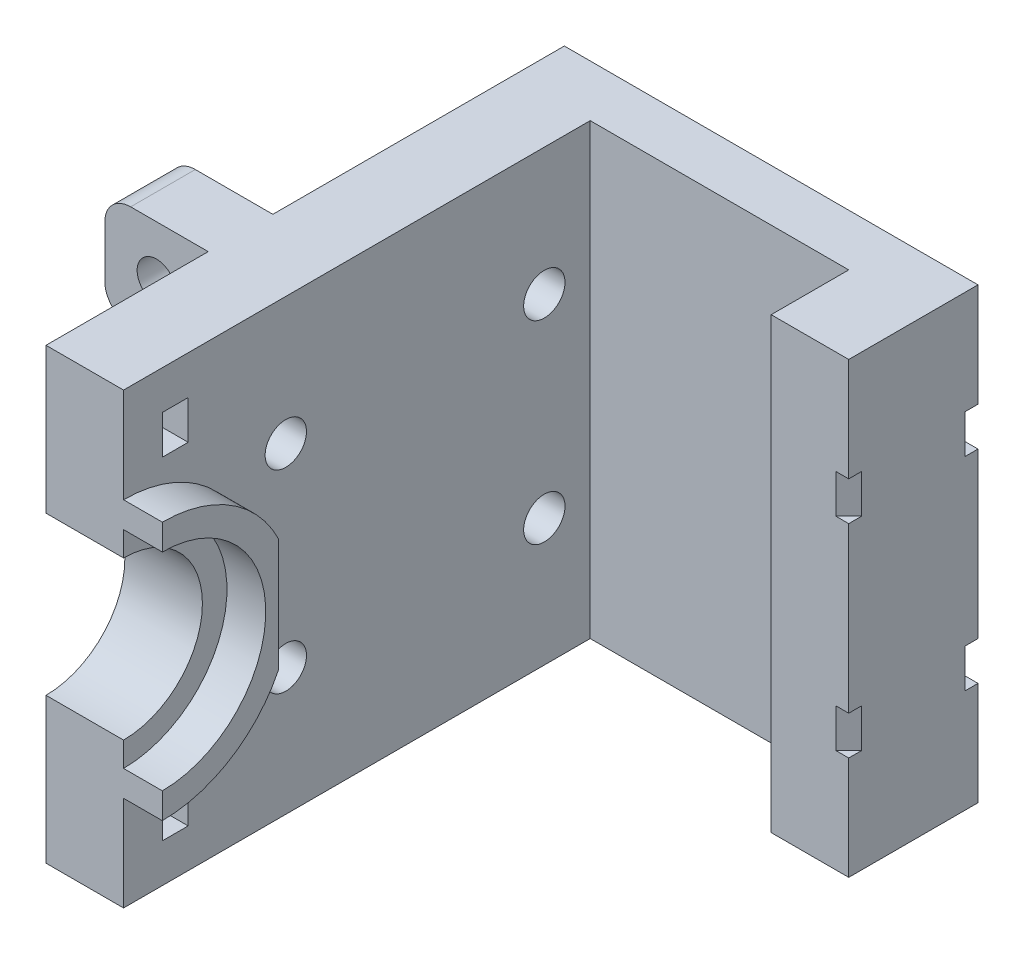
SolidWorks part; units mm, degrees
ref_plane "前基準面" through (0, 0, 0) normal (0, 0, 1) x (1, 0, 0)
ref_plane "上基準面" through (0, 0, 0) normal (0, 1, 0) x (1, 0, 0)
ref_plane "右基準面" through (0, 0, 0) normal (1, 0, 0) x (0, 0, -1)
sketch "草圖2" plane through (0, 0, 0) normal (1, 0, 0) x (0, 0, -1)
  line L1 (-13.55, 17.35) -> (13.55, 17.35)
  line L2 (-13.55, 17.35) -> (-13.55, -17.35) construction
  line L3 (-13.55, -17.35) -> (13.55, -17.35)
  line L4 (13.55, 17.35) -> (13.55, -17.35)
  line L5 (-13.55, 17.35) -> (13.55, -17.35) construction
  line L6 (-13.55, -17.35) -> (13.55, 17.35) construction
  line L7 (-10, 7.5) -> (10, 7.5) construction
  line L8 (-10, 7.5) -> (-10, -7.5) construction
  line L9 (-10, -7.5) -> (10, -7.5) construction
  line L10 (10, 7.5) -> (10, -7.5) construction
  line L11 (-10, 7.5) -> (10, -7.5) construction
  line L12 (-10, -7.5) -> (10, 7.5) construction
  line L13 (-13.55, 17.35) -> (-22.55, 17.35)
  line L14 (-13.55, 17.35) -> (-13.55, -17.35) construction
  line L15 (-13.55, -17.35) -> (-22.55, -17.35)
  line L16 (-22.55, 17.35) -> (-22.55, -17.35)
  line L17 (-19.55, -14.35) -> (-17.55, -14.35)
  line L18 (-19.55, -14.35) -> (-19.55, -11.35)
  line L19 (-19.55, -11.35) -> (-17.55, -11.35)
  line L20 (-17.55, -14.35) -> (-17.55, -11.35)
  line L21 (-19.55, 14.35) -> (-17.55, 14.35)
  line L22 (-19.55, 14.35) -> (-19.55, 11.35)
  line L23 (-19.55, 11.35) -> (-17.55, 11.35)
  line L24 (-17.55, 14.35) -> (-17.55, 11.35)
  circle A0 centre (-10, 7.5) radius 1.6
  circle A1 centre (10, 7.5) radius 1.6
  circle A2 centre (10, -7.5) radius 1.6
  circle A3 centre (-10, -7.5) radius 1.6
  arc A4 (-22.55, -6.1) -> (-22.55, 6.1) centre (-22.55, 0) ccw
  point P0 (0, 0)
  point P6 (0, 0)
  dimension "D5" = 3.2
  dimension "D6" = 3.2
  dimension "D7" = 3.2
  dimension "D8" = 3.2
  dimension "D10" = 6.1
  dimension "D1" = 27.1
  dimension "D2" = 34.7
  dimension "D3" = 20
  dimension "D4" = 15
  dimension "D9" = 9
  dimension "D11" = 2
  dimension "D12" = 3
  dimension "D13" = 3
  dimension "D14" = 3
  dimension "D15" = 3
  dimension "D16" = 3
  dimension "D17" = 3
  dimension "D18" = 2
extrude "填料-伸長1" add sketch "草圖2" along normal blind 6 contours A4 L16 L15 L3 L4 L1 L13 A3 A2 A1 A0 L20 L17 L18 L19 L21 L24 L23 L22
sketch "草圖3" plane through (6, 0, 0) normal (1, 0, 0) x (0, 0, -1)
  line L0 (-22.55, -6.1) -> (-22.55, -17.35) construction
  line L1 (-22.55, 17.35) -> (-22.55, 6.1) construction
  line L2 (-13.55, 4.3589) -> (-13.55, -4.3589)
  line L4 (-22.55, 10) -> (-22.55, 8)
  line L5 (-22.55, -8) -> (-22.55, -10)
  arc A0 (-22.55, -8) -> (-22.55, 8) centre (-22.55, 0) ccw
  arc A1 (-22.55, -10) -> (-13.55, -4.3589) centre (-22.55, 0) ccw
  arc A2 (-13.55, 4.3589) -> (-22.55, 10) centre (-22.55, 0) ccw
  dimension "D1" = 8
  dimension "D2" = 10
  dimension "D3" = 9
extrude "填料-伸長2" add sketch "草圖3" along normal blind 3
sketch "草圖4" plane through (0, 0, 0) normal (-1, 0, 0) x (0, 0, 1)
  line L1 (-13.55, 17.35) -> (-17.55, 17.35)
  line L2 (-13.55, 17.35) -> (-13.55, -17.35)
  line L3 (-13.55, -17.35) -> (-17.55, -17.35)
  line L4 (-17.55, 17.35) -> (-17.55, -17.35)
  dimension "D1" = 4
extrude "填料-伸長3" add sketch "草圖4" against normal blind 26
sketch "草圖5" plane through (26, 0, 0) normal (1, 0, 0) x (0, 0, -1)
  line L0 (13.55, -17.35) -> (-22.55, -17.35) construction
  line L1 (17.55, 17.35) -> (6.55, 17.35)
  line L2 (17.55, 17.35) -> (17.55, -17.35)
  line L3 (17.55, -17.35) -> (6.55, -17.35)
  line L4 (6.55, 17.35) -> (6.55, -17.35)
  dimension "D1" = 11
ref_plane "平面1" through (0, -9.35, 0) normal (0, -1, 0) x (-1, 0, 0)
ref_plane "平面2" through (0, 9.35, 0) normal (0, 1, 0) x (1, 0, 0)
sketch "草圖10" plane through (0, 0, 0) normal (-1, 0, 0) x (0, 0, 1)
  line L1 (-17.55, 17.35) -> (-21.55, 17.35)
  line L2 (-17.55, 17.35) -> (-17.55, -17.35)
  line L3 (-17.55, -17.35) -> (-21.55, -17.35)
  line L4 (-21.55, 17.35) -> (-21.55, -17.35)
  dimension "D1" = 4
sketch "草圖15" plane through (26, 0, 0) normal (1, 0, 0) x (0, 0, -1)
  line L0 (17.55, -17.35) -> (6.55, -17.35) construction
  line L1 (17.55, 17.35) -> (7.55, 17.35)
  line L2 (17.55, 17.35) -> (17.55, -17.35)
  line L3 (17.55, -17.35) -> (7.55, -17.35)
  line L4 (7.55, 17.35) -> (7.55, -17.35)
  dimension "D1" = 10
extrude "填料-伸長8" add sketch "草圖15" along normal blind 6
sketch "草圖16" plane through (0, 0, -17.55) normal (0, 0, -1) x (-1, 0, 0)
  line L0 (-26, 17.35) -> (-26, -17.35) construction
  line L1 (-26, 9.35) -> (-24, 9.35)
  line L2 (-26, 9.35) -> (-26, 6.35)
  line L3 (-26, 6.35) -> (-24, 6.35)
  line L4 (-24, 9.35) -> (-24, 6.35)
  line L5 (14.3, 9.35) -> (-14.3, 9.35) construction
  line L6 (-14.3, -9.35) -> (14.3, -9.35) construction
  line L7 (-26, -9.35) -> (-24, -9.35)
  line L8 (-26, -9.35) -> (-26, -6.35)
  line L9 (-26, -6.35) -> (-24, -6.35)
  line L10 (-24, -9.35) -> (-24, -6.35)
  dimension "D1" = 2
  dimension "D2" = 3
  dimension "D3" = 2
  dimension "D4" = 3
extrude "除料-伸長4" cut sketch "草圖16" against normal blind 6
sketch "草圖17" plane through (0, -9.35, 0) normal (0, -1, 0) x (-1, 0, 0)
  line L0 (-32, 17.55) -> (-31, 17.55)
  line L1 (-32, 17.55) -> (0, 17.55) construction
  line L2 (-31, 17.55) -> (-32, 16.55)
  line L3 (-32, 7.55) -> (-32, 17.55) construction
  line L4 (-32, 16.55) -> (-32, 17.55)
  line L5 (-32, 7.55) -> (-32, 8.55)
  line L6 (-32, 8.55) -> (-31, 7.55)
  line L7 (-32, 7.55) -> (-26, 7.55) construction
  line L8 (-31, 7.55) -> (-32, 7.55)
  dimension "D1" = 1
  dimension "D2" = 1
  dimension "D3" = 1
  dimension "D4" = 1
extrude "除料-伸長5" cut sketch "草圖17" against normal blind 3
sketch "草圖18" plane through (0, 9.35, 0) normal (0, 1, 0) x (1, 0, 0)
  line L0 (32, 17.55) -> (31, 17.55)
  line L1 (32, 17.55) -> (0, 17.55) construction
  line L2 (31, 17.55) -> (32, 16.55)
  line L3 (32, 16.55) -> (32, 17.55)
  line L4 (32, 7.55) -> (32, 8.55)
  line L5 (32, 17.55) -> (32, 7.55) construction
  line L6 (32, 8.55) -> (31, 7.55)
  line L7 (32, 7.55) -> (26, 7.55) construction
  line L8 (31, 7.55) -> (32, 7.55)
  dimension "D1" = 1
  dimension "D2" = 1
  dimension "D3" = 1
  dimension "D4" = 1
extrude "除料-伸長6" cut sketch "草圖18" against normal blind 3
sketch "草圖19" plane through (0, 0, 0) normal (-1, 0, 0) x (0, 0, 1)
  line L0 (10, 7.5) -> (10, 17.35) construction
  line L1 (22.55, 17.35) -> (-17.55, 17.35) construction
  line L2 (-17.55, -17.35) -> (22.55, -17.35) construction
  line L5 (8.3973, 13.7664) -> (11.3973, 13.7664)
  line L6 (11.3973, 17.35) -> (11.3973, 13.7664)
  line L8 (8.3973, 13.7664) -> (10, 17.35) construction
  line L9 (8.5, -20.35) -> (11.5, -20.35)
  line L10 (8.5, -20.35) -> (8.5, -14.35)
  line L11 (8.5, -14.35) -> (11.5, -14.35)
  line L12 (11.5, -20.35) -> (11.5, -14.35)
  line L13 (8.5, -20.35) -> (11.5, -14.35) construction
  line L14 (8.5, -14.35) -> (11.5, -20.35) construction
  line L15 (8.3973, 17.35) -> (11.3973, 17.35)
  line L18 (8.3973, 17.35) -> (8.3973, 13.7664)
  line L19 (10, 17.35) -> (11.3973, 13.7664) construction
  point P9 (10, -17.35)
  dimension "D1" = 3
  dimension "D2" = 3
  dimension "D3" = 3.5836
  dimension "D4" = 6
sketch "草圖20" plane through (0, 17.35, 0) normal (0, 1, 0) x (1, 0, 0)
  line L0 (0, 5) -> (-8, 5) construction
  line L1 (0, -22.55) -> (0, 17.55) construction
  line L2 (-8, 5) -> (-8, -5) construction
  line L3 (-8, -5) -> (0, -5) construction
  line L4 (0, -5) -> (0, 5) construction
  line L5 (10.0883, 0) -> (-16.5311, 0) construction
  line L7 (0, -5) -> (-8, -5)
  line L8 (0, -5) -> (0, -10)
  line L9 (0, -10) -> (-8, -10)
  line L10 (-8, -5) -> (-8, -10)
  dimension "D1" = 8
  dimension "D2" = 10
  dimension "D3" = 8
  dimension "D4" = 5
extrude "填料-伸長9" add sketch "草圖20" against normal blind 40
sketch "草圖22" plane through (0, 0, 10) normal (0, 0, 1) x (1, 0, 0)
  line L0 (-4, 17.35) -> (-4, -21.6931) construction
  line L1 (-8, 17.35) -> (0, 17.35) construction
  circle A0 centre (-4, 13.35) radius 1.5
  circle A1 centre (-4, -18.65) radius 1.5
  point P8 (0, 0)
  dimension "D1" = 32
  dimension "D3" = 3
  dimension "D2" = 4
extrude "除料-伸長7" cut sketch "草圖22" against normal blind 10
sketch "草圖23" plane through (0, 0, 10) normal (0, 0, 1) x (1, 0, 0)
  line L0 (-8, -22.65) -> (-8, 17.35) construction
  line L1 (-8, 9.35) -> (0, 9.35)
  line L2 (-8, 9.35) -> (-8, -14.65)
  line L3 (-8, -14.65) -> (0, -14.65)
  line L4 (0, 9.35) -> (0, -14.65)
  line L5 (0, 17.35) -> (0, -17.35) construction
  circle A0 centre (-4, 13.35) radius 1.5 construction
  circle A1 centre (-4, -18.65) radius 1.5 construction
  dimension "D1" = 4
  dimension "D2" = 4
extrude "除料-伸長8" cut sketch "草圖23" against normal blind 10
fillet "圓角4" radius 5 1 edges at (0, -14.65, 7.5)
fillet "圓角5" radius 2 1 edges at (0, -17.35, 7.5)
fillet "圓角6" radius 2 4 edges at (-8, 9.35, 7.5) (-8, -14.65, 7.5) (-8, -22.65, 7.5) (-8, 17.35, 7.5)
fillet "圓角7" radius 2 1 edges at (0, -22.65, 7.5)
